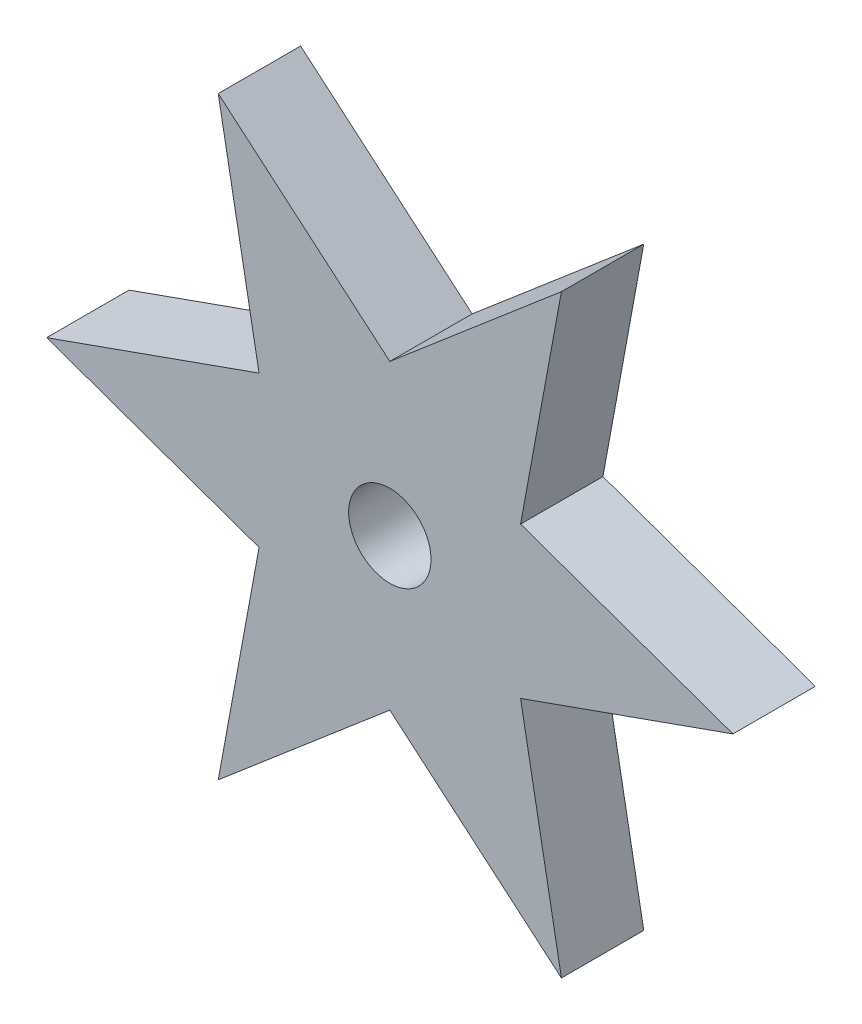
SolidWorks part; units mm, degrees
ref_plane "Front Plane" through (0, 0, 0) normal (0, 0, 1) x (1, 0, 0)
ref_plane "Top Plane" through (0, 0, 0) normal (0, 1, 0) x (1, 0, 0)
ref_plane "Right Plane" through (0, 0, 0) normal (1, 0, 0) x (0, 0, -1)
sketch "Sketch1" plane through (0, 0, 0) normal (0, 0, 1) x (1, 0, 0)
  line L0 (12.5, 0) -> (4.7631, 2.75)
  line L1 (4.7631, 2.75) -> (6.25, 10.8253)
  line L2 (6.25, 10.8253) -> (0, 5.5)
  line L3 (0, 5.5) -> (-6.25, 10.8253)
  line L4 (-6.25, 10.8253) -> (-4.7631, 2.75)
  line L5 (-4.7631, 2.75) -> (-12.5, 0)
  line L6 (-12.5, 0) -> (-4.7631, -2.75)
  line L7 (-4.7631, -2.75) -> (-6.25, -10.8253)
  line L8 (-6.25, -10.8253) -> (0, -5.5)
  line L9 (0, -5.5) -> (6.25, -10.8253)
  line L10 (6.25, -10.8253) -> (4.7631, -2.75)
  line L11 (4.7631, -2.75) -> (12.5, 0)
  circle A0 centre (0, 0) radius 1.5
extrude "Boss-Extrude1" add sketch "Sketch1" along normal blind 3
